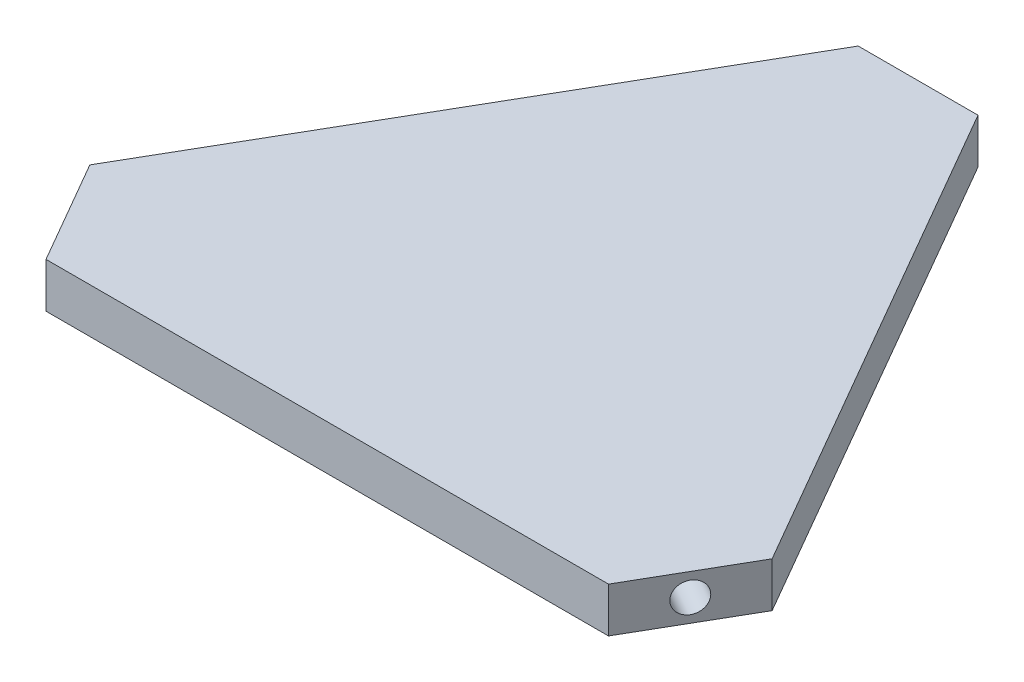
SolidWorks part; units mm, degrees
ref_plane "Front Plane" through (0, 0, 0) normal (0, 0, 1) x (1, 0, 0)
ref_plane "Top Plane" through (0, 0, 0) normal (0, 1, 0) x (1, 0, 0)
ref_plane "Right Plane" through (0, 0, 0) normal (1, 0, 0) x (0, 0, -1)
sketch "Sketch1" plane through (0, 0, 0) normal (0, 1, 0) x (1, 0, 0)
  line L0 (12.7, 76.2) -> (-12.7, 76.2)
  line L1 (-12.7, 76.2) -> (-72.3411, -27.1015)
  line L2 (-59.6411, -49.0985) -> (59.6411, -49.0985)
  line L3 (72.3411, -27.1015) -> (12.7, 76.2)
  line L4 (-72.3411, -27.1015) -> (-59.6411, -49.0985)
  line L5 (72.3411, -27.1015) -> (59.6411, -49.0985)
  line L6 (0, 0) -> (0, 76.2) construction
  line L7 (0, 0) -> (65.9911, -38.1) construction
  line L8 (0, 0) -> (-65.9911, -38.1) construction
  circle A0 centre (0, 0) radius 49.0985 construction
  point P2 (38.2087, -74.702)
  point P3 (0, 0)
  point P4 (0, 76.2)
  point P12 (75.3279, -21.9282)
  dimension "D1" = 76.2
  dimension "D2" = 25.4
extrude "Boss-Extrude1" add sketch "Sketch1" along normal mid plane 9.525
hole_wizard "1/4 (0.25) Diameter Hole1" positions "Sketch4" profile "Sketch5" hole size "1/4" standard "ANSI Inch"
sketch "Sketch4" plane through (65.9911, 0, 38.1) normal (0.866, 0, 0.5) x (0.5, 0, -0.866)
  point P0 (0, 0)
sketch "Sketch5" plane through (65.9911, 0, 38.1) normal (0, 1, 0) x (0.5, 0, -0.866)
  line L0 (0, 0) -> (0, 14.6077)
  line L1 (0, 14.6077) -> (3.175, 12.7)
  line L2 (3.175, 12.7) -> (3.175, 0)
  line L5 (3.175, 0) -> (0, 0)
  line L10 (0, 14.6077) -> (-3.175, 12.7) construction
  line L11 (0, -6.35) -> (0, 107.95) construction
  dimension "Hole Dia." = 6.35
  dimension "Hole Depth" = 12.7
  dimension "Drill Angle" = 118
pattern_circular "CirPattern1" count 3 over 360 about axis through (0, 4.7625, 0) along (0, 1, 0) of "1/4 (0.25) Diameter Hole1"
